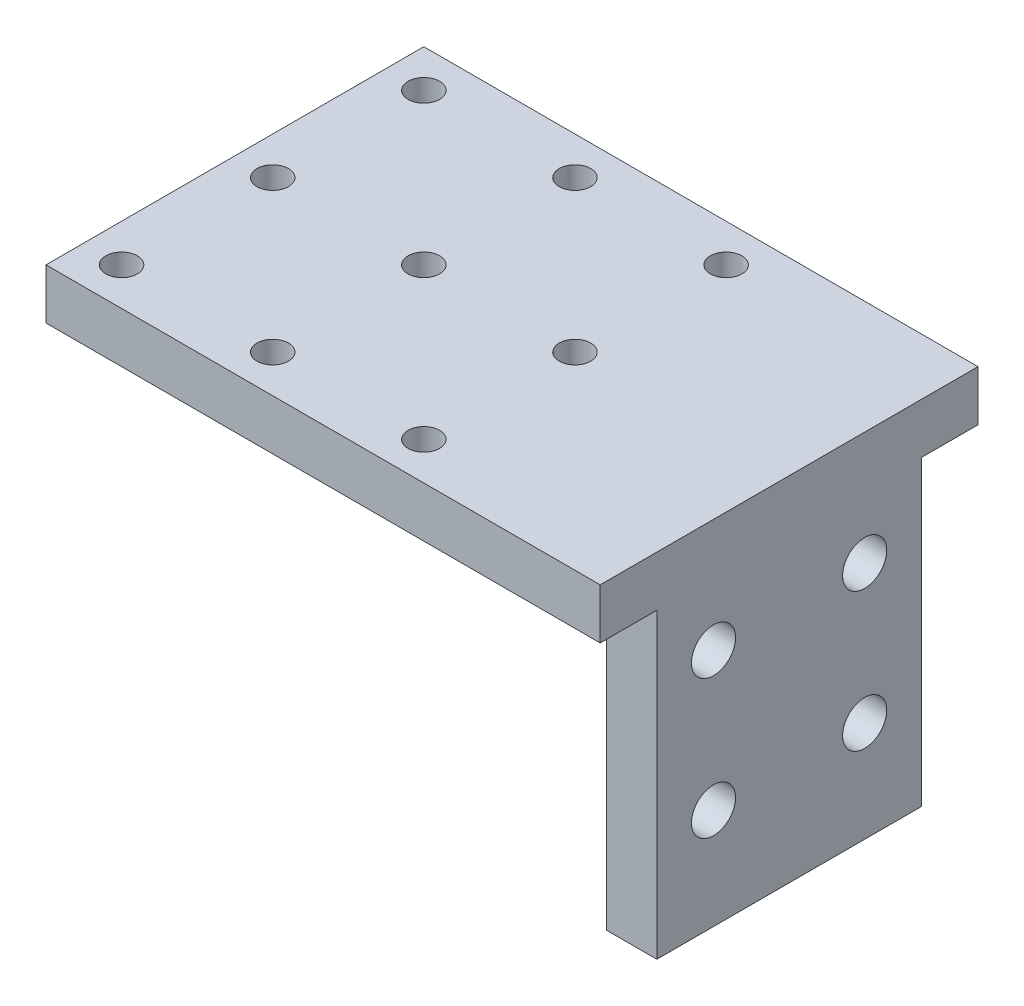
SolidWorks part; units mm, degrees
material "PBT Общее назначение"
ref_plane "Спереди" through (0, 0, 0) normal (0, 0, 1) x (1, 0, 0)
ref_plane "Сверху" through (0, 0, 0) normal (0, 1, 0) x (1, 0, 0)
ref_plane "Справа" through (0, 0, 0) normal (1, 0, 0) x (0, 0, -1)
sketch "Эскиз1" plane through (0, 0, 0) normal (0, 0, 1) x (1, 0, 0)
  line L0 (0, 0) -> (0, 24)
  line L1 (0, 24) -> (-40, 24)
  line L2 (-40, 24) -> (-40, 28)
  line L3 (-40, 28) -> (4, 28)
  line L4 (4, 28) -> (4, 0)
  line L5 (4, 0) -> (0, 0)
  dimension "D1" = 4
  dimension "D2" = 40
  dimension "D3" = 24
extrude "Бобышка-Вытянуть1" add sketch "Эскиз1" against normal blind 30
sketch "Эскиз2" plane through (0, 28, 0) normal (0, 1, 0) x (1, 0, 0)
  line L0 (-37, 3) -> (-37, 27) construction
  line L1 (-37, 3) -> (-13, 3) construction
  line L2 (-37, 27) -> (-13, 27) construction
  line L3 (-13, 3) -> (-13, 27) construction
  line L4 (-40, 30) -> (-40, 0) construction
  line L5 (4, 0) -> (-40, 0) construction
  line L6 (-37, 15) -> (-13, 15) construction
  circle A0 centre (-37, 3) radius 1.25
  circle A1 centre (-13, 3) radius 1.25
  circle A2 centre (-37, 27) radius 1.25
  circle A3 centre (-37, 15) radius 1.25
  circle A4 centre (-25, 27) radius 1.25
  circle A5 centre (-13, 27) radius 1.25
  circle A6 centre (-13, 15) radius 1.25
  circle A7 centre (-25, 3) radius 1.25
  circle A8 centre (-25, 15) radius 1.25
  dimension "D5" = 2.5
  dimension "D1" = 24
  dimension "D2" = 24
  dimension "D3" = 3
  dimension "D4" = 3
extrude "Вырез-Вытянуть1" cut sketch "Эскиз2" against normal through all
sketch "Эскиз3" plane through (0, 28, 0) normal (0, 1, 0) x (1, 0, 0)
  line L0 (-40, 15) -> (4, 15) construction
  line L1 (-40, 30) -> (-40, 0) construction
  line L2 (4, 30) -> (4, 0) construction
ref_plane "Плоскость1" through (0, 0, -15) normal (0, 0, 1) x (1, 0, 0)
sketch "Эскиз4" plane through (0, 0, 0) normal (0, 0, 1) x (1, 0, 0)
  line L0 (0, 0) -> (4, 0)
  line L1 (0, 0) -> (0, 24)
  line L2 (4, 0) -> (4, 24)
  line L3 (0, 24) -> (4, 24)
  line L4 (-40, 24) -> (0, 24) construction
extrude "Вырез-Вытянуть2" cut sketch "Эскиз4" against normal blind 4.5
mirror "Зеркальное отражение1" about plane through (0, 0, -15) normal (0, 0, 1) of "Вырез-Вытянуть2"
sketch "Эскиз5" plane through (4, 0, 0) normal (1, 0, 0) x (0, 0, -1)
  line L0 (9, 19) -> (21, 19) construction
  line L1 (9, 19) -> (9, 8) construction
  line L2 (21, 19) -> (21, 8) construction
  line L3 (9, 8) -> (21, 8) construction
  line L4 (15, 28) -> (15, 0) construction
  line L5 (25.5, 0) -> (4.5, 0) construction
  circle A0 centre (9, 19) radius 1.75
  circle A1 centre (21, 19) radius 1.75
  circle A2 centre (21, 8) radius 1.75
  circle A3 centre (9, 8) radius 1.75
  point P6 (15, 19)
  dimension "D4" = 3.5
  dimension "D1" = 8
  dimension "D2" = 11
  dimension "D3" = 12
extrude "Вырез-Вытянуть3" cut sketch "Эскиз5" against normal through all
sketch "Эскиз7" plane through (0, 0, 0) normal (-1, 0, 0) x (0, 0, 1)
  line L0 (-15, 0) -> (-15, 24) construction
  line L1 (-25.5, 0) -> (-4.5, 0) construction
  line L2 (-25.5, 24) -> (-4.5, 24) construction
sketch "Эскиз8" plane through (0, 0, -15) normal (0, 0, 1) x (1, 0, 0)
  line L0 (0, 0) -> (0, 24) construction
  line L1 (0, 0) -> (0, 24)
  line L2 (0, 24) -> (-8, 24)
  line L3 (-8, 24) -> (0, 0)
  dimension "D1" = 8
extrude "Бобышка-Вытянуть2" add sketch "Эскиз8" along normal blind 2 and the other way blind 2
